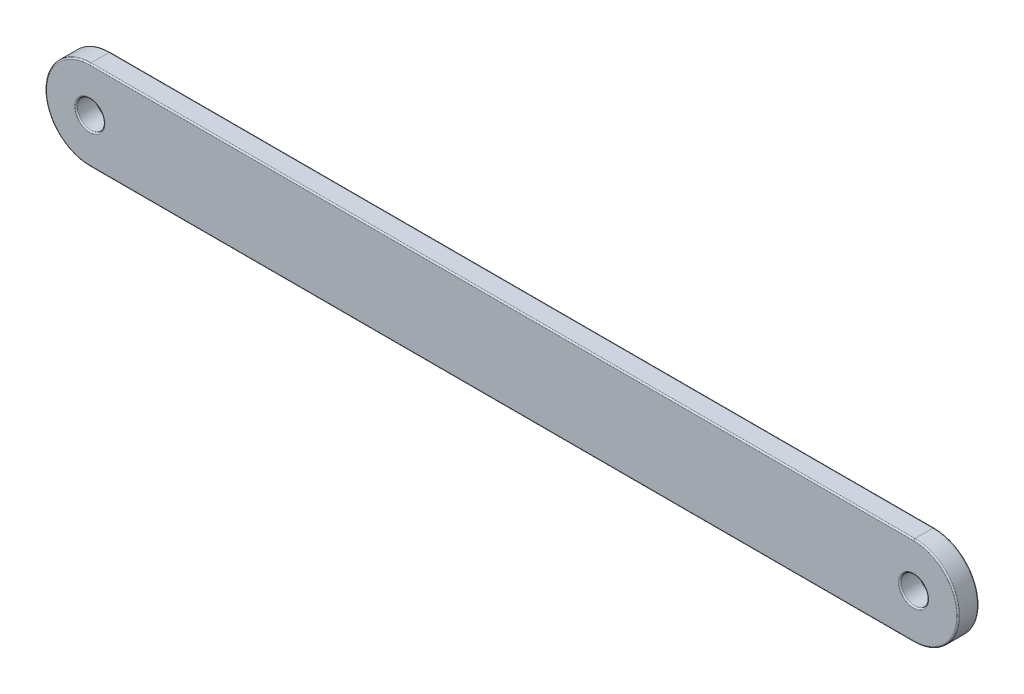
SolidWorks part; units mm, degrees
ref_plane "Front Plane" through (0, 0, 0) normal (0, 0, 1) x (1, 0, 0)
ref_plane "Top Plane" through (0, 0, 0) normal (0, 1, 0) x (1, 0, 0)
ref_plane "Right Plane" through (0, 0, 0) normal (1, 0, 0) x (0, 0, -1)
sketch "Sketch1" plane through (0, 0, 0) normal (0, 0, 1) x (1, 0, 0)
  line L0 (-30, 0) -> (30, 0) construction
  line L1 (-30, 3.25) -> (30, 3.25)
  line L2 (-30, -3.25) -> (30, -3.25)
  arc A0 (-30, 3.25) -> (-30, -3.25) centre (-30, 0) ccw
  arc A1 (30, -3.25) -> (30, 3.25) centre (30, 0) ccw
  circle A2 centre (-30, 0) radius 1
  circle A3 centre (30, 0) radius 1
  point P2 (0, 0)
  dimension "D2" = 3.25
  dimension "D3" = 2
  dimension "D1" = 60
extrude "Boss-Extrude1" add sketch "Sketch1" along normal mid plane 1.5
fillet "Fillet1" radius 0.1 12 edges at (31, 0, -0.75) (-29, 0, -0.75) (0, -3.25, -0.75) (33.25, 0, -0.75) (0, 3.25, -0.75) (-33.25, 0, -0.75) (31, 0, 0.75) (0, 3.25, 0.75) (33.25, 0, 0.75) (0, -3.25, 0.75) (-33.25, 0, 0.75) (-29, 0, 0.75)
